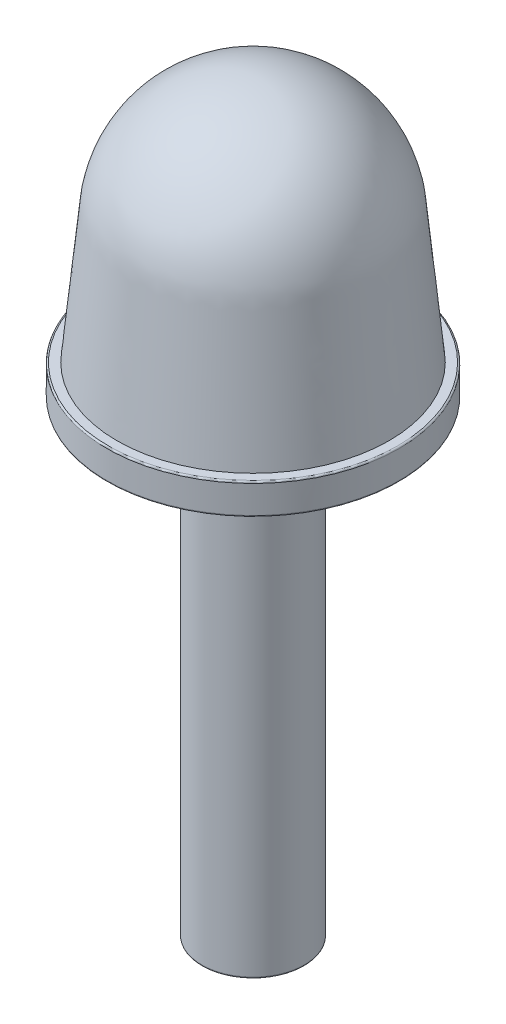
SolidWorks part; units mm, degrees
ref_plane "Front Plane" through (0, 0, 0) normal (0, 0, 1) x (1, 0, 0)
ref_plane "Top Plane" through (0, 0, 0) normal (0, 1, 0) x (1, 0, 0)
ref_plane "Right Plane" through (0, 0, 0) normal (1, 0, 0) x (0, 0, -1)
sketch "Sketch1" plane through (0, 0, 0) normal (0, 0, 1) x (1, 0, 0)
  line L0 (0, 0) -> (0, -72.5)
  line L1 (11.9413, -10.8148) -> (13.25, -24) construction
  line L2 (13.25, -24) -> (14.25, -24)
  line L3 (14.25, -24) -> (14.25, -27)
  line L4 (14.25, -27) -> (9, -27)
  line L5 (9, -27) -> (9, -30)
  line L6 (9, -30) -> (5, -30)
  line L7 (5, -30) -> (5, -72.5)
  line L8 (5, -72.5) -> (0, -72.5)
  arc A0 (0, 0) -> (11.9413, -10.8148) centre (0, -12) cw construction
  spline S0 degree 3 poles (13.25, -24) (12.8763, -20.2348) (12.5026, -16.4695) (12.1289, -12.7043) (12.108, -12.4944) (12.0664, -12.0745) (12.0038, -11.4446) (11.9622, -11.0247) (11.9413, -10.8148) (11.9136, -10.5354) (11.8581, -9.9768) (11.6666, -9.149) (11.5141, -8.6083) (11.4285, -8.3409) (9.7791, -3.189) (5.4095, 0) (0, 0) knots 0 0 0 0 0.379321 0.379321 0.379321 0.400472 0.421623 0.442773 0.442773 0.442773 0.470915 0.499057 0.527199 0.527199 0.527199 1 1 1 1 weights 1 1 1 1 1 1 1 1 1 1 1 1 1 1 0.871834 0.871834 1
  dimension "D1" = 72.5
  dimension "D2" = 12
  dimension "D3" = 1
  dimension "D4" = 3
  dimension "D5" = 24
  dimension "D6" = 14.25
  dimension "D7" = 9
  dimension "D8" = 3
  dimension "D9" = 5
revolve "Revolve1" add sketch "Sketch1" angle 360 about L0
sketch "Sketch2" plane through (0, 0, 0) normal (0, 0, 1) x (1, 0, 0)
  line L0 (14.25, -24) -> (-14.25, -24) construction
  circle A0 centre (0, -11.75) radius 6.125
  dimension "D1" = 12.25
  dimension "D2" = 12.25
sketch "Sketch3" plane through (0, 0, 0) normal (1, 0, 0) x (0, 0, -1)
  line L0 (0, 0) -> (0, -24) construction
  line L1 (14.25, -24) -> (-14.25, -24) construction
  line L2 (21.544, -24) -> (21.544, 0)
  line L3 (-9.75, -24) -> (-21.544, -24)
  line L4 (-7.25, -21.5) -> (-7.25, 0)
  line L5 (-7.25, 0) -> (-21.544, 0)
  line L6 (-21.544, -24) -> (-21.544, 0)
  line L7 (7.25, 0) -> (21.544, 0)
  line L8 (7.25, -21.5) -> (7.25, 0)
  line L9 (9.75, -24) -> (21.544, -24)
  arc A0 (-9.75, -24) -> (-7.25, -21.5) centre (-9.75, -21.5) ccw
  arc A1 (9.75, -24) -> (7.25, -21.5) centre (9.75, -21.5) cw
  point P11 (-7.25, -24)
  point P18 (7.25, -24)
  dimension "D2" = 2.5
  dimension "D1" = 14.5
fillet "Fillet2" radius 0.15 6 edges at (-5, -72.5, 0) (-5, -30, 0) (-9, -30, 0) (-9, -27, 0) (-14.25, -27, 0) (-14.25, -24, 0)
